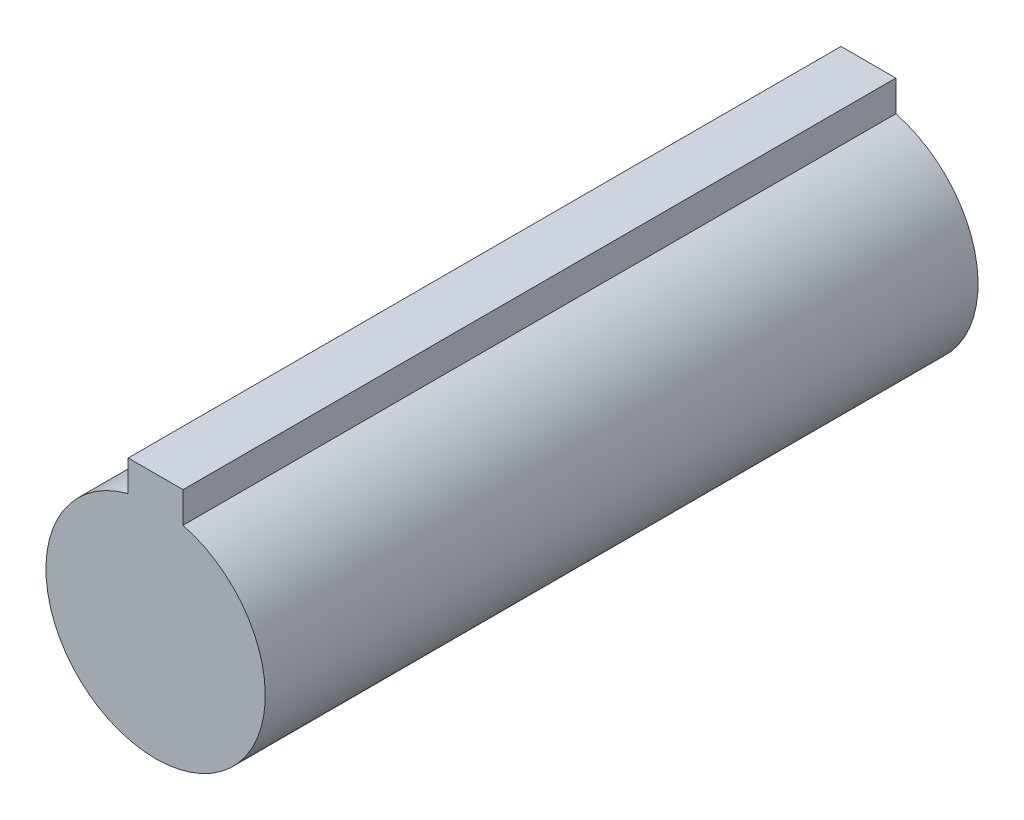
SolidWorks part; units mm, degrees
ref_plane "Front" through (0, 0, 0) normal (0, 0, 1) x (1, 0, 0)
ref_plane "Top" through (0, 0, 0) normal (0, 1, 0) x (1, 0, 0)
ref_plane "Right" through (0, 0, 0) normal (1, 0, 0) x (0, 0, -1)
sketch "Sketch1" plane through (0, 0, 0) normal (0, 0, 1) x (1, 0, 0)
  line L3 (-5, 25) -> (-5, 19.3649)
  line L4 (5, 25) -> (-5, 25)
  line L5 (5, 19.3649) -> (5, 25)
  arc A1 (-5, 19.3649) -> (5, 19.3649) centre (0, 0) ccw
extrude "Extrude1" add sketch "Sketch1" against normal blind 120 and the other way blind 10
